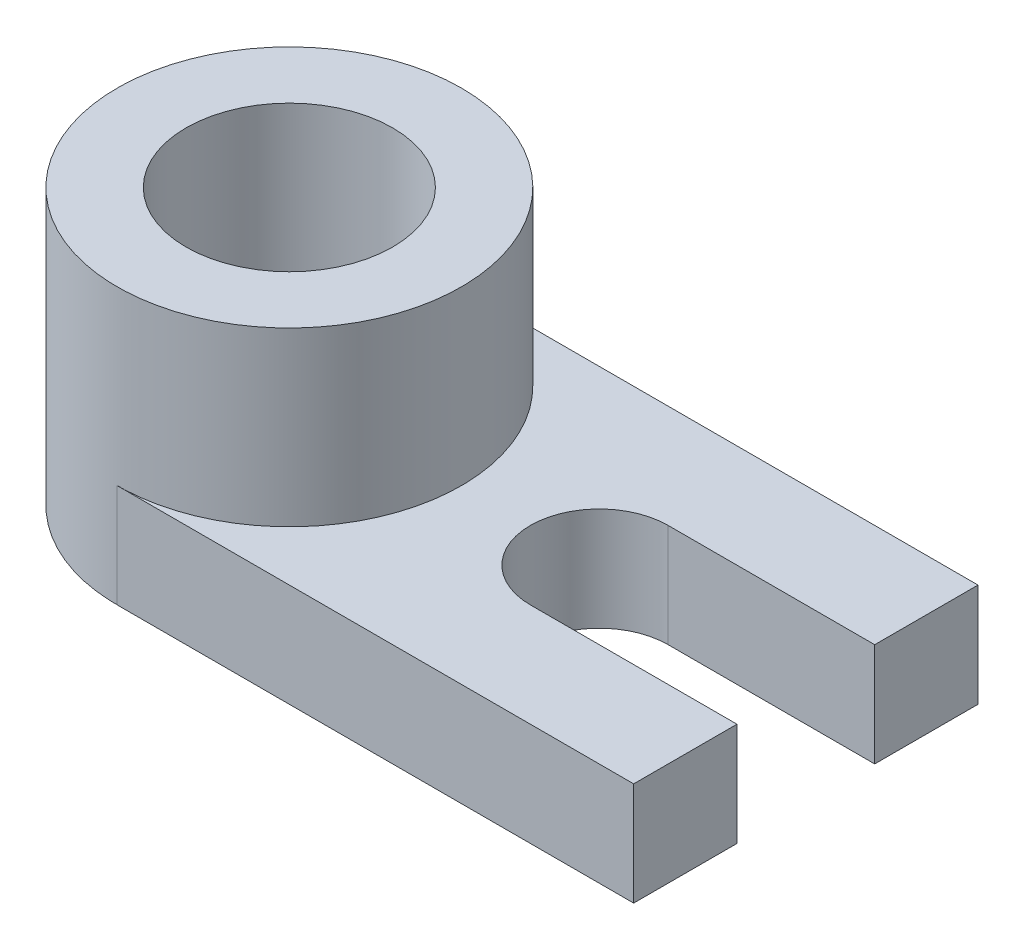
SolidWorks part; units mm, degrees
ref_plane "Front Plane" through (0, 0, 0) normal (0, 0, 1) x (1, 0, 0)
ref_plane "Top Plane" through (0, 0, 0) normal (0, 1, 0) x (1, 0, 0)
ref_plane "Right Plane" through (0, 0, 0) normal (1, 0, 0) x (0, 0, -1)
sketch "Sketch1" plane through (0, 0, 0) normal (0, 1, 0) x (1, 0, 0)
  line L1 (0, 50) -> (75, 50)
  line L2 (0, 50) -> (0, 0)
  line L3 (0, 0) -> (75, 0)
  line L4 (75, 50) -> (75, 0)
  point P4 (0, 0)
  dimension "D1" = 50
  dimension "D2" = 75
extrude "Boss-Extrude1" add sketch "Sketch1" along normal blind 15
sketch "Sketch2" plane through (0, 0, 0) normal (0, -1, 0) x (1, 0, 0)
  line L0 (0, -50) -> (0, 0) construction
  line L1 (0, 0) -> (75, 0) construction
  circle A0 centre (0, -25) radius 25
  point P2 (0, -25)
extrude "Boss-Extrude2" add sketch "Sketch2" against normal blind 40 separate body
sketch "Sketch3" plane through (0, 40, 0) normal (0, 1, 0) x (1, 0, 0)
  circle A0 centre (0, 25) radius 15
  dimension "D1" = 30
extrude "Cut-Extrude1" cut sketch "Sketch3" against normal through all contours A0
hole_wizard "Ø20.0 (20) Diameter Hole1" positions "Sketch6" profile "Sketch5" hole size "Ø20.0" standard "ANSI Metric" end condition through all
sketch "Sketch6" plane through (0, 15, 0) normal (0, 1, 0) x (1, 0, 0)
  line L0 (75, 0) -> (75, 50) construction
  line L1 (75, 50) -> (0, 50) construction
  point P0 (45, 25)
  point P3 (0, 0)
  point P4 (0, 0)
  point P5 (0, 0)
  dimension "D1" = 30
  dimension "D2" = 25
sketch "Sketch5" plane through (45, 15, -25) normal (1, 0, 0) x (0, 0, 1)
  line L0 (0, 0) -> (0, 15)
  line L1 (0, 15) -> (10, 15)
  line L2 (10, 15) -> (10, 0)
  line L5 (10, 0) -> (0, 0)
  line L11 (0, -6.35) -> (0, 107.95) construction
  dimension "Thru Hole Dia." = 20
  dimension "Thru Hole Depth" = 15
sketch "Sketch7" plane through (75, 0, 0) normal (1, 0, 0) x (0, 0, -1)
  line L0 (0, 15) -> (50, 15) construction
  line L1 (15, 15) -> (35, 15)
  line L2 (15, 15) -> (15, 0)
  line L3 (15, 0) -> (35, 0)
  line L4 (35, 15) -> (35, 0)
  dimension "D1" = 20
extrude "Cut-Extrude2" cut sketch "Sketch7" against normal up to next
